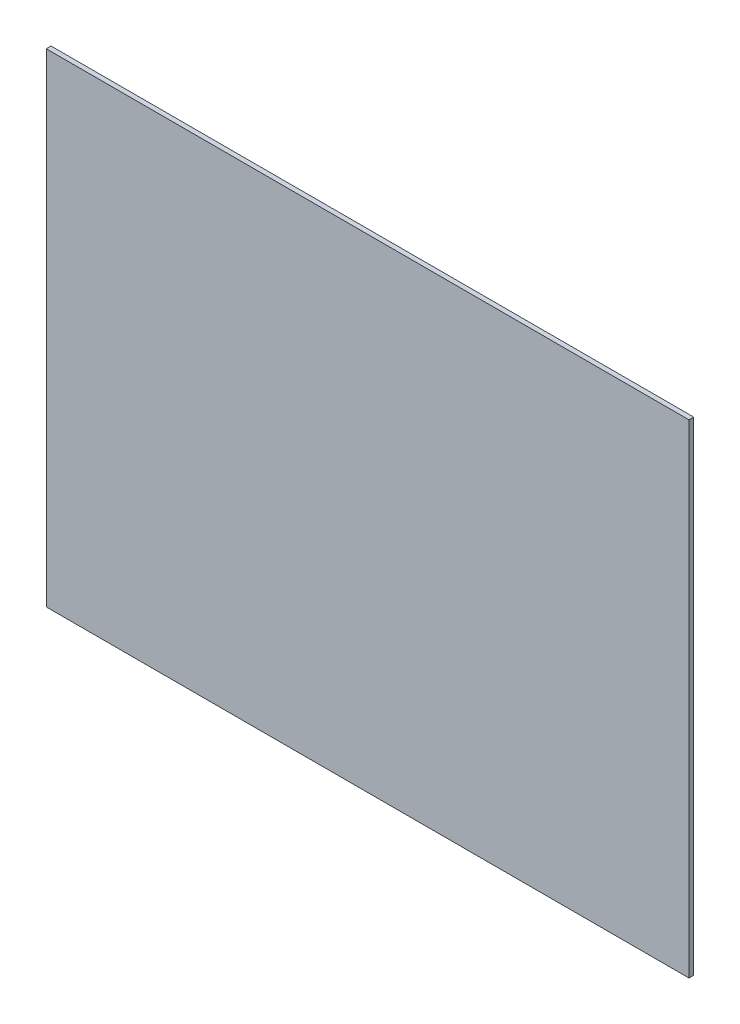
SolidWorks part; units mm, degrees
ref_plane "Спереди" through (0, 0, 0) normal (0, 0, 1) x (1, 0, 0)
ref_plane "Сверху" through (0, 0, 0) normal (0, 1, 0) x (1, 0, 0)
ref_plane "Справа" through (0, 0, 0) normal (1, 0, 0) x (0, 0, -1)
sketch "Эскиз1" plane through (0, 0, 0) normal (0, 0, 1) x (1, 0, 0)
  line L1 (-403.5, 303.5) -> (403.5, 303.5)
  line L2 (-403.5, 303.5) -> (-403.5, -303.5)
  line L3 (-403.5, -303.5) -> (403.5, -303.5)
  line L4 (403.5, 303.5) -> (403.5, -303.5)
  line L5 (-403.5, 303.5) -> (403.5, -303.5) construction
  line L6 (-403.5, -303.5) -> (403.5, 303.5) construction
  point P0 (0, 0)
  dimension "D1" = 607
  dimension "D2" = 807
extrude "Бобышка-Вытянуть1" add sketch "Эскиз1" along normal blind 6
